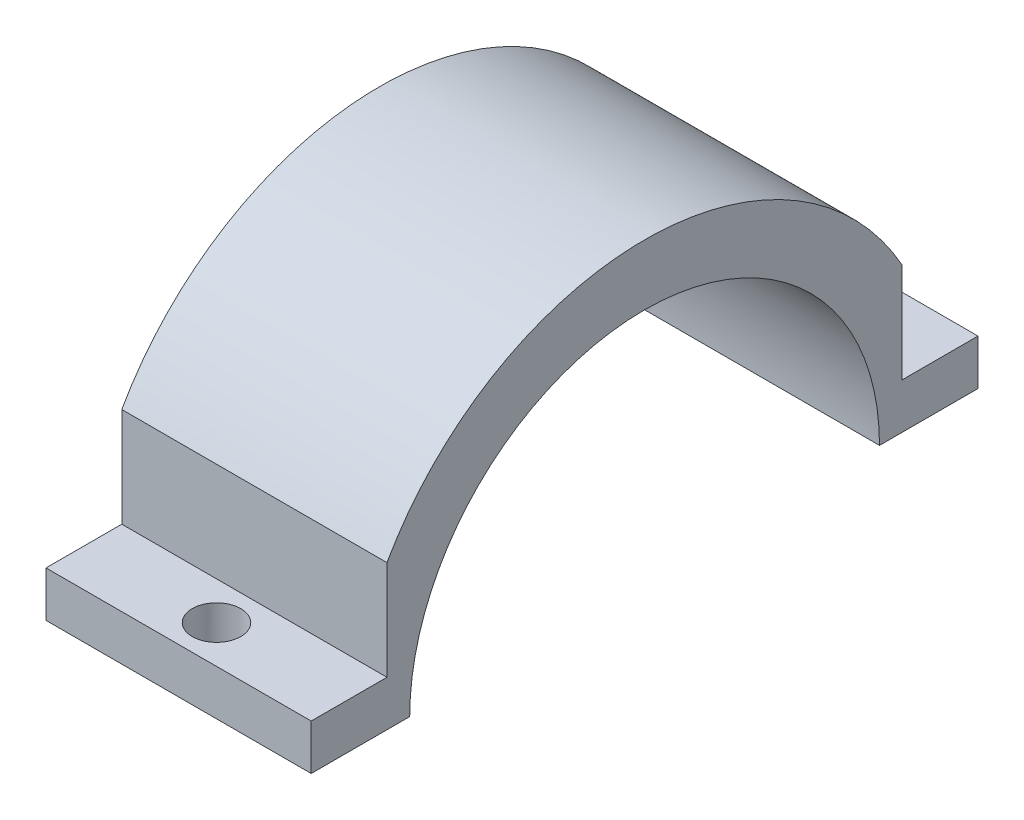
SolidWorks part; units mm, degrees
ref_plane "前视基准面" through (0, 0, 0) normal (0, 0, 1) x (1, 0, 0)
ref_plane "上视基准面" through (0, 0, 0) normal (0, 1, 0) x (1, 0, 0)
ref_plane "右视基准面" through (0, 0, 0) normal (1, 0, 0) x (0, 0, -1)
sketch "草图1" plane through (0, 0, 0) normal (0, 1, 0) x (1, 0, 0)
  line L1 (0, 0) -> (17, 0)
  line L2 (0, 0) -> (0, -40)
  line L3 (0, -40) -> (17, -40)
  line L4 (17, 0) -> (17, -40)
  dimension "D1" = 17
  dimension "D2" = 40
extrude "凸台-拉伸1" add sketch "草图1" along normal blind 50
sketch "草图2" plane through (0, 0, 0) normal (0, -1, 0) x (1, 0, 0)
  line L0 (0, 39) -> (0, 40)
  line L1 (-0.5, 39) -> (17, 39) construction
  line L2 (0, 0) -> (0, 40) construction
  line L3 (0, 40) -> (17, 40)
  line L4 (17, 40) -> (17, 39)
  line L5 (17, 40) -> (17, 0) construction
  line L6 (17, 39) -> (0, 39)
extrude "切除-拉伸1" cut sketch "草图2" against normal through all
sketch "草图4" plane through (0, 0, 0) normal (0, -1, 0) x (1, 0, 0)
  line L2 (-0.5, 0) -> (0, 0)
  line L3 (0, 0) -> (0, 39)
  line L4 (-0.5, 0) -> (-0.5, 39)
  line L5 (-0.5, 39) -> (0, 39)
extrude "凸台-拉伸2" add sketch "草图4" against normal up to vertex (50 mm away) up to point (0, 50, 39)
sketch "草图5" plane through (17, 0, 0) normal (1, 0, 0) x (0, 0, -1)
  circle A0 centre (-22, 4.5) radius 15.5
extrude "切除-拉伸2" cut sketch "草图5" against normal up to vertex (17.5 mm away)
sketch "草图6" plane through (17, 0, 0) normal (1, 0, 0) x (0, 0, -1)
  line L0 (0, 24) -> (0, 3)
  line L2 (-22, 24) -> (-5, 24)
  line L3 (0, 50) -> (0, 0) construction
  line L4 (0, 24) -> (0, 50)
  line L5 (0, 50) -> (-39, 50)
  line L6 (-39, 50) -> (-39, 24)
  line L7 (-39, 50) -> (-39, 0) construction
  line L8 (-39, 24) -> (-22, 24)
  line L9 (0, 0) -> (0, 3)
  line L10 (0, 3) -> (-5, 3)
  line L11 (-5, 3) -> (-5, 24)
  line L12 (0, 24) -> (0, 3)
  line M11 (0, 0) -> (0, 50)
  line M12 (0, 50) -> (-39, 50)
  line M13 (-39, 50) -> (-39, 0)
extrude "切除-拉伸3" cut sketch "草图6" against normal up to vertex (17.5 mm away) contours L11 L10 L8 L2 M11 M12 M13
sketch "草图7" plane through (0, 3, 0) normal (0, 1, 0) x (1, 0, 0)
  line L0 (8.25, -5) -> (8.25, 0)
  line L1 (-0.5, -5) -> (17, -5) construction
  line L2 (-0.5, 0) -> (17, 0) construction
  circle A0 centre (8.25, -2.5) radius 1.6
extrude "切除-拉伸4" cut sketch "草图7" against normal up to vertex (3 mm away) contours L0 A0 | L0 A0
sketch "草图8" plane through (-0.5, 0, 0) normal (-1, 0, 0) x (0, 0, 1)
  line L0 (22, 4.5) -> (5, 4.5)
  line L1 (5, 3) -> (5, 24) construction
  line L2 (22, 4.5) -> (39, 4.5)
  line L3 (39, 24) -> (39, 0) construction
  line L4 (39, 4.5) -> (39, 0)
  line L5 (39, 0) -> (17.2565, -28.4468)
  line L6 (17.2565, -28.4468) -> (-8.6135, 4.5)
  line L7 (-8.6135, 4.5) -> (5, 4.5)
  circle A0 centre (22, 4.5) radius 15.5
  line M2 (5, 24) -> (5, 3)
  line M3 (5, 3) -> (0, 3)
  line M4 (0, 3) -> (0, 0)
  line M5 (0, 0) -> (7.1676, 0)
  arc M6 (7.1676, 0) -> (36.8324, 0) centre (22, 4.5) cw
  line M7 (36.8324, 0) -> (39, 0)
  line M8 (39, 0) -> (39, 24)
extrude "切除-拉伸7" cut sketch "草图8" against normal blind 64 contours A0 L7 L6 L5 M5 M4 M3 M2 M7 | L0 M6 M2 M3 M4 M5 | A0 L2 L0 M6 | L2 M6 M7 M8
sketch "草图9" plane through (-0.5, 0, 0) normal (-1, 0, 0) x (0, 0, 1)
  line L0 (5, 4.5) -> (5, 7.5)
  line L1 (5, 4.5) -> (5, 24) construction
  line L2 (5, 7.5) -> (0, 7.5)
  line L3 (0, 7.5) -> (0, 4.5)
  line L4 (0, 4.5) -> (5, 4.5)
  line L5 (39, 4.5) -> (39, 7.5)
  line L6 (39, 24) -> (39, 4.5) construction
  line L7 (39, 7.5) -> (44, 7.5)
  line L8 (44, 7.5) -> (44, 4.5)
  line L9 (44, 4.5) -> (39, 4.5)
extrude "凸台-拉伸3" add sketch "草图9" against normal up to vertex (17.5 mm away)
sketch "草图10" plane through (-0.5, 0, 0) normal (-1, 0, 0) x (0, 0, 1)
  line L0 (6.5, 4.5) -> (37.5, 4.5)
  line L1 (5, 14.0525) -> (5, 24)
  line L2 (5, 7.5) -> (5, 24) construction
  line L3 (5, 24) -> (39, 24)
  line L4 (39, 24) -> (39, 14.0525)
  line L5 (39, 24) -> (39, 7.5) construction
  arc A0 (39, 14.0525) -> (5, 14.0525) centre (22, 4.5) ccw
  line M1 (5, 24) -> (5, 7.5)
  line M9 (39, 7.5) -> (39, 24)
  line M10 (39, 24) -> (5, 24)
extrude "切除-拉伸8" cut sketch "草图10" against normal through all and the other way through all contours A0 L3 M1 | A0 M9 M10
sketch "草图11" plane through (0, 7.5, 0) normal (0, 1, 0) x (1, 0, 0)
  line L0 (8.25, -5) -> (8.25, 0)
  line L1 (17, -5) -> (-0.5, -5) construction
  line L2 (17, 0) -> (-0.5, 0) construction
  line L3 (8.25, -39) -> (8.25, -44)
  line L4 (17, -39) -> (-0.5, -39) construction
  line L5 (17, -44) -> (-0.5, -44) construction
  circle A0 centre (8.25, -2.5) radius 1.6
  circle A1 centre (8.25, -41.5) radius 1.6
extrude "切除-拉伸9" cut sketch "草图11" against normal blind 64 contours L0 A0 | L0 A0 | L3 A1 | L3 A1
